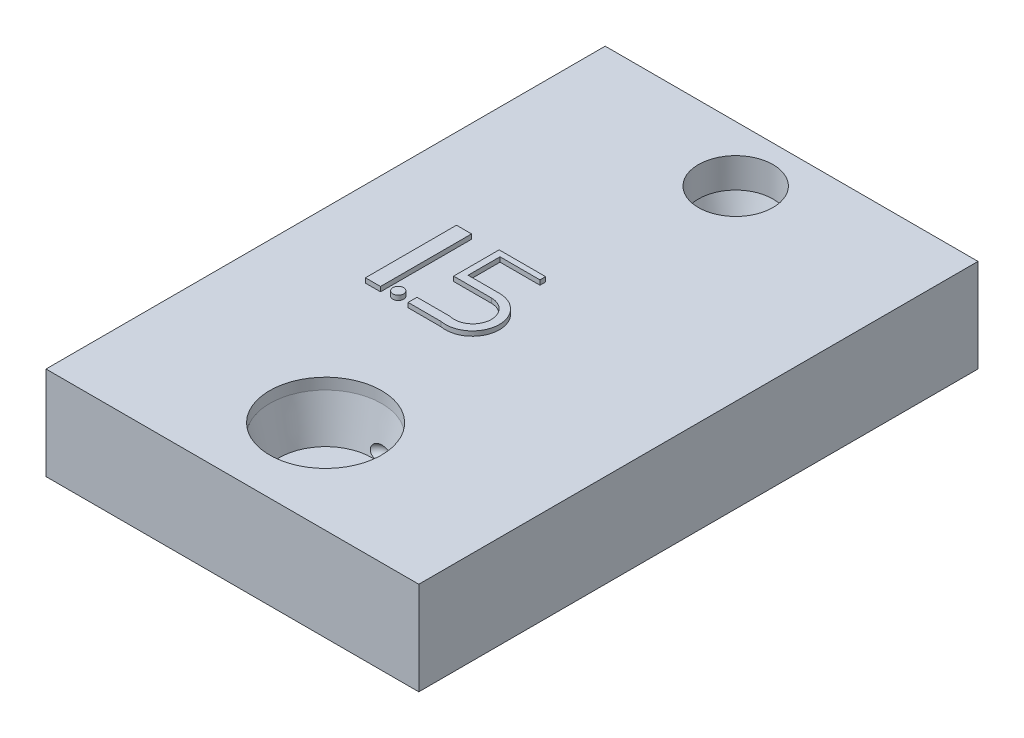
SolidWorks part; units mm, degrees
ref_plane "Front Plane" through (0, 0, 0) normal (0, 0, 1) x (1, 0, 0)
ref_plane "Top Plane" through (0, 0, 0) normal (0, 1, 0) x (1, 0, 0)
ref_plane "Right Plane" through (0, 0, 0) normal (1, 0, 0) x (0, 0, -1)
sketch "Sketch1" plane through (0, 0, 0) normal (0, 0, 1) x (1, 0, 0)
  line L1 (-20, 5) -> (20, 5)
  line L2 (-20, 5) -> (-20, -5)
  line L3 (-20, -5) -> (20, -5)
  line L4 (20, 5) -> (20, -5)
  line L5 (-20, 5) -> (20, -5) construction
  line L6 (-20, -5) -> (20, 5) construction
  point P0 (0, 0)
  dimension "D1" = 10
  dimension "D2" = 40
extrude "Boss-Extrude1" add sketch "Sketch1" along normal blind 60
ref_plane "Plane1" through (0, 0, 0) normal (0, 1, 0) x (1, 0, 0)
sketch "Sketch2" plane through (0, 0, 0) normal (0, 1, 0) x (1, 0, 0)
  line L1 (-20, -60) -> (20, -60) construction
  line L5 (0, -50) -> (0, -46)
  line L6 (1, -45) -> (15, -45)
  line L7 (15, -42) -> (0, -42)
  line L8 (0, -42) -> (-15, -42)
  line L9 (-15, -39) -> (15, -39)
  line L10 (15, -36) -> (-15, -36)
  line L11 (-15, -33) -> (15.3556, -33)
  line L12 (15.3556, -30) -> (-15, -30)
  line L13 (-15, -27) -> (15, -27)
  line L14 (15, -24) -> (-15, -24)
  line L15 (-15, -21) -> (15, -21)
  line L16 (15, -18) -> (-15, -18)
  line L17 (-15, -15) -> (15, -15)
  line L18 (15, -12) -> (1, -12)
  line L19 (0, -11) -> (0, -6)
  arc A0 (15, -45) -> (15, -42) centre (15, -43.5) ccw
  arc A1 (-15, -42) -> (-15, -39) centre (-15, -40.5) cw
  arc A2 (15, -39) -> (15, -36) centre (15, -37.5) ccw
  arc A3 (-15, -36) -> (-15, -33) centre (-15, -34.5) cw
  arc A4 (15.3556, -33) -> (15.3556, -30) centre (15.3556, -31.5) ccw
  arc A5 (-15, -30) -> (-15, -27) centre (-15, -28.5) cw
  arc A6 (15, -27) -> (15, -24) centre (15, -25.5) ccw
  arc A7 (-15, -24) -> (-15, -21) centre (-15, -22.5) cw
  arc A8 (15, -21) -> (15, -18) centre (15, -19.5) ccw
  arc A9 (-15, -18) -> (-15, -15) centre (-15, -16.5) cw
  arc A10 (15, -15) -> (15, -12) centre (15, -13.5) ccw
  arc A11 (0, -46) -> (1, -45) centre (1, -46) cw
  arc A12 (1, -12) -> (0, -11) centre (1, -11) cw
  point P5 (0, -45)
  point P9 (0, -12)
  dimension "D5" = 1
  dimension "D1" = 10
  dimension "D2" = 5
  dimension "D3" = 15
  dimension "D4" = 15
  dimension "D16" = 6
ref_plane "Plane2" through (0, 0, 6) normal (0, 0, -1) x (-1, 0, 0)
sketch "Sketch10" plane through (0, 0, 6) normal (0, 0, -1) x (-1, 0, 0)
  circle A0 centre (0, 0) radius 0.75
  dimension "D1" = 1.5
sketch "Sketch11" plane through (0, 0, 6) normal (0, 0, -1) x (-1, 0, 0)
sweep "Cut-Sweep1" cut profiles "Sketch10" path "Sketch2"
ref_plane "Plane4" through (0, 0, 0) normal (1, 0, 0) x (0, 0, -1)
sketch "Sketch13" plane through (0, 0, 0) normal (1, 0, 0) x (0, 0, -1)
  line L0 (-50, -0.75) -> (-55, -0.75)
  line L2 (-50, -0.75) -> (-50, 29.25)
  line L3 (-50, 29.25) -> (-56, 29.25)
  line L4 (-56, 29.25) -> (-56, 3.8)
  line L5 (-56, 3.8) -> (-55, -0.75)
  dimension "D1" = 5
  dimension "D3" = 6
  dimension "D4" = 30
revolve "Cut-Revolve1" cut sketch "Sketch13" angle 360 about L2
sketch "Sketch14" plane through (0, 0, 0) normal (1, 0, 0) x (0, 0, -1)
  line L0 (-6, -0.75) -> (-3, -0.75)
  line L2 (-6, -0.75) -> (-6, 29.25)
  line L3 (-6, 29.25) -> (-2, 29.25)
  line L4 (-2, 29.25) -> (-2, 1.8)
  line L5 (-2, 1.8) -> (-3, -0.75)
  dimension "D1" = 3
  dimension "D3" = 30
  dimension "D4" = 4
revolve "Cut-Revolve2" cut sketch "Sketch14" angle 360 about L2
sketch "Sketch15" plane through (0, 5, 0) normal (0, 1, 0) x (1, 0, 0)
  line L0 (-20, -30) -> (20, -30) construction
  line L1 (-20, -60) -> (-20, 0) construction
  line L2 (20, -60) -> (20, 0) construction
  line L3 (-1.2792, -25.1156) -> (-6.2616, -25.1156)
  line L4 (-10.8399, -25.1156) -> (-9.224, -25.1156)
  line L5 (-10.8399, -25.1156) -> (-10.8399, -34.8844)
  line L6 (-10.8399, -34.8844) -> (-9.224, -34.8844)
  line L7 (-9.224, -25.1156) -> (-9.224, -34.8844)
  line L8 (-10.8399, -25.1156) -> (-9.224, -34.8844) construction
  line L9 (-10.8399, -34.8844) -> (-9.224, -25.1156) construction
  line L10 (-6.2616, -25.1156) -> (-6.2616, -30)
  line L11 (-6.2616, -30) -> (-2.2091, -30)
  line L12 (-1.2792, -25.1156) -> (-1.2792, -25.7156)
  line L13 (-1.2792, -25.7156) -> (-5.5708, -25.7156)
  line L14 (-5.5708, -25.7156) -> (-5.5708, -27.5578)
  line L15 (-5.5708, -27.5578) -> (-5.5708, -29.1422)
  line L16 (-5.5708, -29.1422) -> (-2.2091, -29.1422)
  line L17 (-6.2616, -34.8844) -> (-6.2616, -33.929)
  line L18 (-6.2616, -33.929) -> (-2.7206, -33.929)
  line L19 (-6.2616, -34.8844) -> (-2.7206, -34.8844)
  arc A0 (-2.2091, -30) -> (-2.7206, -33.929) centre (-2.2091, -31.9978) cw
  arc A1 (-2.2091, -29.1422) -> (-2.7206, -34.8844) centre (-2.2091, -32.0361) cw
  circle A2 centre (-7.8728, -34.331) radius 0.5828
  point P6 (-10.032, -30)
  dimension "D1" = 0.6
extrude "Boss-Extrude2" add sketch "Sketch15" along normal blind 0.5
